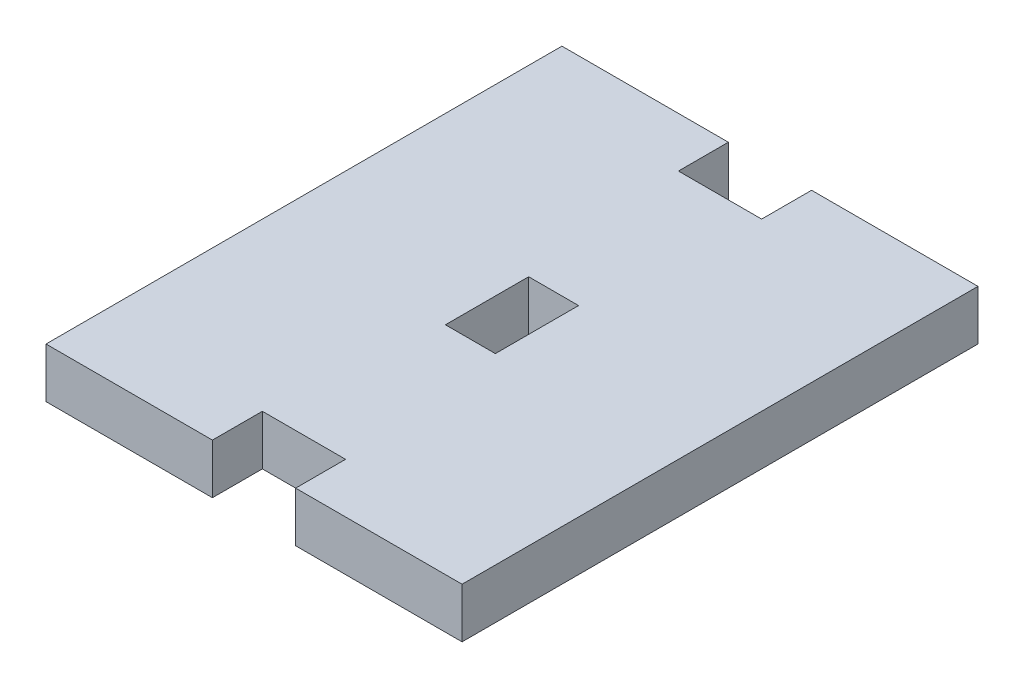
SolidWorks part; units mm, degrees
ref_plane "Plano frontal" through (0, 0, 0) normal (0, 0, 1) x (1, 0, 0)
ref_plane "Plano superior" through (0, 0, 0) normal (0, 1, 0) x (1, 0, 0)
ref_plane "Plano direito" through (0, 0, 0) normal (1, 0, 0) x (0, 0, -1)
sketch "Esboço1" plane through (0, 0, 0) normal (0, 1, 0) x (1, 0, 0)
  line L1 (25, -31) -> (-25, -31)
  line L2 (25, -31) -> (25, 31)
  line L3 (25, 31) -> (-25, 31)
  line L4 (-25, -31) -> (-25, 31)
  line L5 (25, -31) -> (-25, 31) construction
  line L6 (25, 31) -> (-25, -31) construction
  point P0 (0, 0)
  dimension "D1" = 50
  dimension "D2" = 62
extrude "Ressalto-extrusão2" add sketch "Esboço1" along normal blind 6
sketch "Esboço3" plane through (0, 0, 31) normal (0, 0, 1) x (1, 0, 0)
  line L0 (-25, 6) -> (25, 6) construction
  line L1 (-5, 6) -> (5, 6)
  line L2 (-5, 6) -> (-5, 0)
  line L3 (-5, 0) -> (5, 0)
  line L4 (5, 6) -> (5, 0)
  line L5 (-25, 0) -> (25, 0) construction
  line L6 (-25, 6) -> (-25, 0) construction
  line L7 (25, 6) -> (25, 0) construction
  dimension "D1" = 20
  dimension "D2" = 20
extrude "Corte-extrusão1" cut sketch "Esboço3" against normal blind 6
sketch "Esboço4" plane through (0, 0, -31) normal (0, 0, -1) x (-1, 0, 0)
  line L0 (-25, 6) -> (25, 6) construction
  line L1 (-5, 6) -> (5, 6)
  line L2 (-5, 6) -> (-5, 0)
  line L3 (-5, 0) -> (5, 0)
  line L4 (5, 6) -> (5, 0)
  line L5 (-25, 0) -> (25, 0) construction
  line L6 (-25, 6) -> (-25, 0) construction
  line L7 (25, 6) -> (25, 0) construction
  dimension "D1" = 20
  dimension "D2" = 20
extrude "Corte-extrusão2" cut sketch "Esboço4" against normal blind 6
sketch "Esboço5" plane through (0, 6, 0) normal (0, 1, 0) x (1, 0, 0)
  line L0 (-25, 0) -> (25, 0) construction
  line L1 (-25, 31) -> (-25, -31) construction
  line L2 (25, -31) -> (25, 31) construction
  line L3 (0, 25) -> (0, -25) construction
  line L4 (-5, 25) -> (5, 25) construction
  line L5 (5, -25) -> (-5, -25) construction
  line L7 (3, -5) -> (-3, -5)
  line L8 (3, -5) -> (3, 5)
  line L9 (3, 5) -> (-3, 5)
  line L10 (-3, -5) -> (-3, 5)
  line L11 (3, -5) -> (-3, 5) construction
  line L12 (3, 5) -> (-3, -5) construction
  point P12 (0, 0)
  dimension "D1" = 6
  dimension "D2" = 10
extrude "Corte-extrusão3" cut sketch "Esboço5" against normal blind 6
